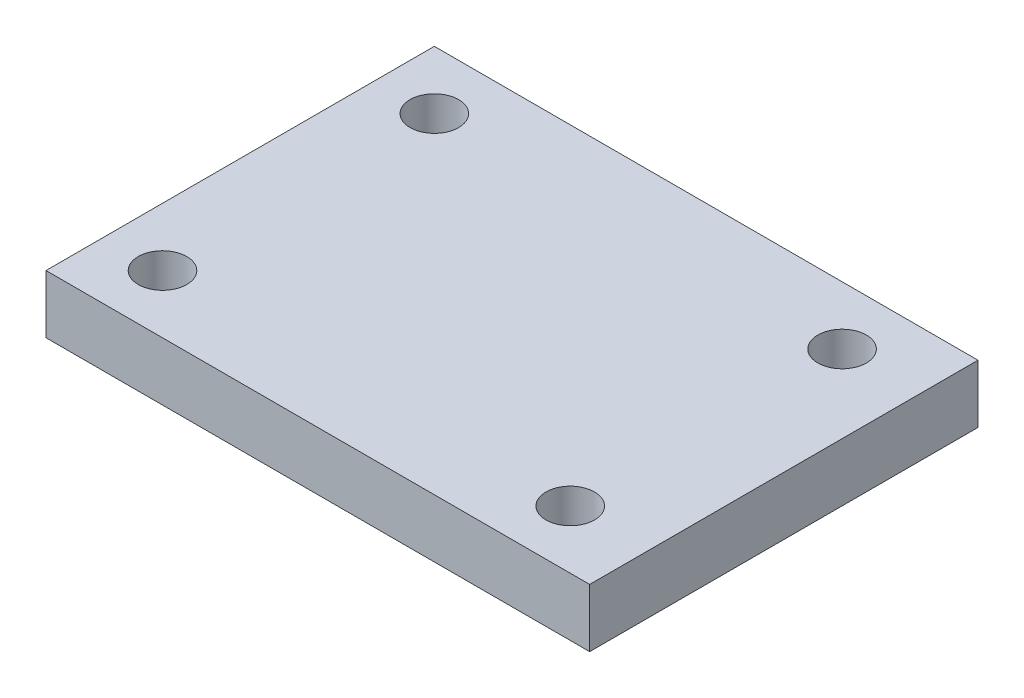
SolidWorks part; units mm, degrees
ref_plane "Front Plane" through (0, 0, 0) normal (0, 0, 1) x (1, 0, 0)
ref_plane "Top Plane" through (0, 0, 0) normal (0, 1, 0) x (1, 0, 0)
ref_plane "Right Plane" through (0, 0, 0) normal (1, 0, 0) x (0, 0, -1)
sketch "Sketch2" plane through (0, 0, 0) normal (0, 1, 0) x (1, 0, 0)
  line L1 (-14, 10) -> (14, 10)
  line L2 (-14, 10) -> (-14, -10)
  line L3 (-14, -10) -> (14, -10)
  line L4 (14, 10) -> (14, -10)
  line L5 (-14, 10) -> (14, -10) construction
  line L6 (-14, -10) -> (14, 10) construction
  point P0 (0, 0)
  dimension "D1" = 20
  dimension "D2" = 28
extrude "Boss-Extrude1" add sketch "Sketch2" along normal blind 3
hole_wizard "M3 Tapped Hole1" positions "Sketch3" profile "Sketch4" tap size "M3" standard "DIN" end condition through all
sketch "Sketch3" plane through (0, 3, 0) normal (0, 1, 0) x (1, 0, 0)
  line L0 (-14, 10) -> (-14, -10) construction
  line L1 (14, 10) -> (-14, 10) construction
  point P0 (-11, 7)
  point P2 (-11, -7)
  point P4 (10, -7)
  point P6 (10, 7)
  point P9 (0, 0)
  point P10 (0, 0)
  point P11 (0, 0)
  dimension "D1" = 14
  dimension "D2" = 21
  dimension "D3" = 3
  dimension "D4" = 3
sketch "Sketch4" plane through (-11, 3, -7) normal (1, 0, 0) x (0, 0, 1)
  line L0 (0, 0) -> (0, 3)
  line L1 (0, 3) -> (1.25, 3)
  line L2 (1.25, 3) -> (1.25, 0)
  line L5 (1.25, 0) -> (0, 0)
  line L11 (0, -6.35) -> (0, 107.95) construction
  dimension "Thru Tap Drill Dia." = 2.5
  dimension "Thru Tap Drill Depth" = 3
cosmetic thread "Hole Thread1" parameters "D2"=3
cosmetic thread "Hole Thread2" parameters "D2"=3
cosmetic thread "Hole Thread3" parameters "D2"=3
cosmetic thread "Hole Thread4" parameters "D2"=3
